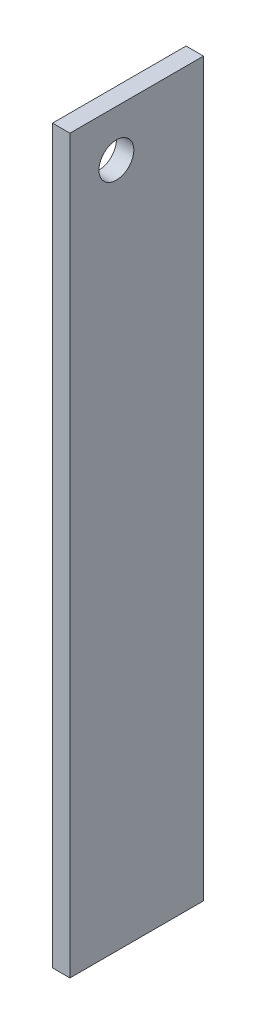
SolidWorks part; units mm, degrees
material "6061-T6 (SS)"
ref_plane "Front" through (0, 0, 0) normal (0, 0, 1) x (1, 0, 0)
ref_plane "Top" through (0, 0, 0) normal (0, 1, 0) x (1, 0, 0)
ref_plane "Right" through (0, 0, 0) normal (1, 0, 0) x (0, 0, -1)
sketch "Sketch1" plane through (0, 0, 0) normal (0, 1, 0) x (1, 0, 0)
  line L1 (-76.2, 584.2) -> (76.2, 584.2)
  line L2 (-76.2, 584.2) -> (-76.2, -584.2)
  line L3 (-76.2, -584.2) -> (76.2, -584.2)
  line L4 (76.2, 584.2) -> (76.2, -584.2)
  line L5 (-76.2, 584.2) -> (76.2, -584.2) construction
  line L6 (-76.2, -584.2) -> (76.2, 584.2) construction
  point P0 (0, 0)
  dimension "D1" = 1168.4
  dimension "D2" = 152.4
extrude "Boss-Extrude1" add sketch "Sketch1" along normal blind 6400.8
sketch "Sketch2" plane through (76.2, 0, 0) normal (1, 0, 0) x (0, 0, -1)
  line L0 (584.2, 6400.8) -> (584.2, 0) construction
  line L1 (584.2, 0) -> (-381, 0)
  line L2 (584.2, 0) -> (584.2, 4267.2)
  line L3 (584.2, 4267.2) -> (-381, 4267.2)
  line L4 (-381, 0) -> (-381, 4267.2)
  line L6 (-584.2, 0) -> (584.2, 0) construction
  dimension "D1" = 965.2
  dimension "D2" = 4267.2
extrude "Cut-Extrude1" [suppressed] cut sketch "Sketch2" against normal through all
sketch "Sketch3" [suppressed] plane through (76.2, 0, 0) normal (1, 0, 0) x (0, 0, -1)
  line L0 (-584.2, 7010.4) -> (-584.2, 0) construction
  line L1 (-584.2, 2743.2) -> (330.2, 2743.2)
  line L2 (-584.2, 2743.2) -> (-584.2, 609.6)
  line L3 (-584.2, 609.6) -> (330.2, 609.6)
  line L4 (-330.2, 609.6) -> (584.2, 609.6)
  line L5 (-330.2, 2743.2) -> (-330.2, 609.6)
  line L6 (584.2, 2743.2) -> (-330.2, 2743.2)
  line L7 (584.2, 609.6) -> (584.2, 2743.2)
  line L8 (-330.2, 609.6) -> (584.2, 609.6) construction
  line L9 (-330.2, 2743.2) -> (-330.2, 609.6) construction
  line L10 (584.2, 2743.2) -> (-330.2, 2743.2) construction
  line L11 (584.2, 609.6) -> (584.2, 2743.2) construction
  line L12 (330.2, 2743.2) -> (330.2, 609.6)
  point P10 (-127, 2743.2)
  dimension "D1" = 0
extrude "Cut-Extrude2" [suppressed] cut sketch "Sketch3" against normal through all
sketch "Sketch4" plane through (-76.2, 0, 0) normal (-1, 0, 0) x (0, 0, 1)
  line L0 (-584.2, 6400.8) -> (584.2, 6400.8) construction
  line L1 (584.2, 6400.8) -> (584.2, 0) construction
  circle A0 centre (177.8, 5994.4) radius 152.4
  dimension "D1" = 304.8
  dimension "D2" = 406.4
  dimension "D3" = 406.4
extrude "Cut-Extrude3" cut sketch "Sketch4" against normal through all and the other way through all
sketch "Sketch5" [suppressed] plane through (-76.2, 0, 0) normal (-1, 0, 0) x (0, 0, 1)
  line L0 (584.2, 6400.8) -> (584.2, 0) construction
  line L1 (-584.2, 0) -> (584.2, 0) construction
  circle A0 centre (177.8, 406.4) radius 152.4
  dimension "D1" = 304.8
  dimension "D2" = 406.4
  dimension "D3" = 406.4
extrude "Cut-Extrude4" [suppressed] cut sketch "Sketch5" against normal through all
